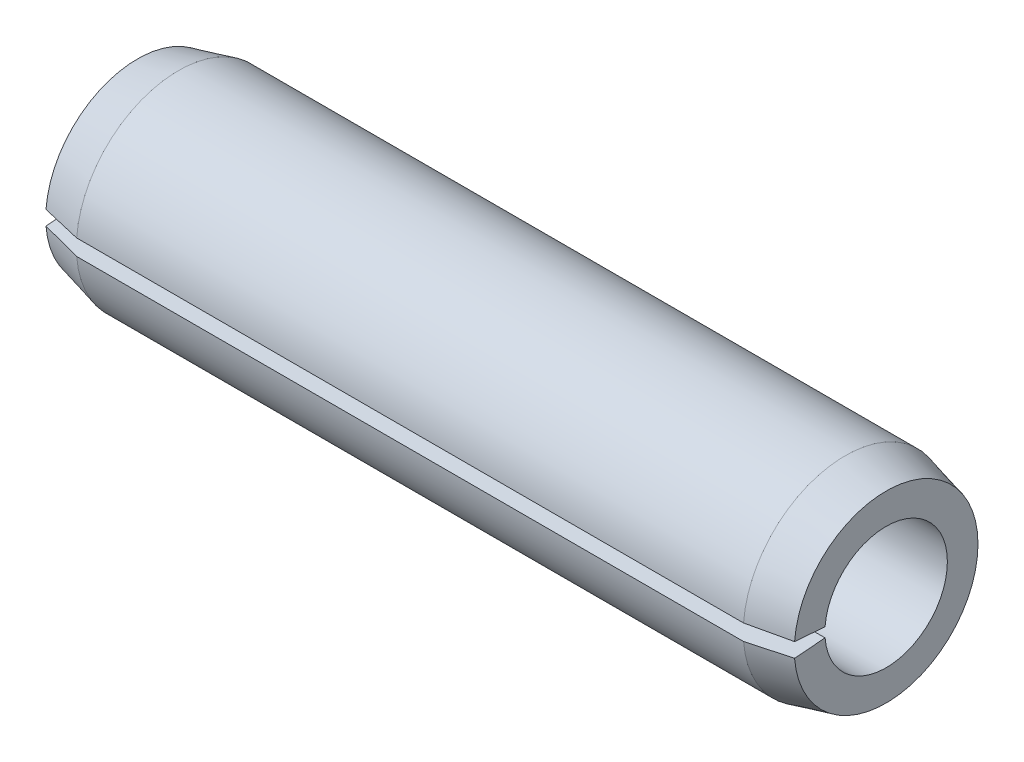
SolidWorks part; units mm, degrees
ref_plane "Plane1" through (0, 0, 0) normal (0, 0, 1) x (1, 0, 0)
ref_plane "Plane2" through (0, 0, 0) normal (0, 1, 0) x (1, 0, 0)
ref_plane "Plane3" through (0, 0, 0) normal (1, 0, 0) x (0, 0, -1)
other "Configuration Table"
sketch "Sketch1" plane through (0, 0, 0) normal (0, 0, 1) x (1, 0, 0)
  line L0 (-9.525, 0) -> (111.125, 0) construction
  line L1 (0, 1.8) -> (22, 1.8)
  line L2 (22, 1.8) -> (22, 2.7)
  line L3 (22, 2.7) -> (20.8, 3)
  line L4 (20.8, 3) -> (1.2, 3)
  line L5 (1.2, 3) -> (0, 2.7)
  line L7 (0, 2.7) -> (0, 1.8)
  dimension "Thickness" = 1.2
  dimension "Length" = 22
revolve "Base-Revolve" add sketch "Sketch1" angle 360 about L0
sketch "Sketch2" plane through (0, 0, 0) normal (-1, 0, 0) x (0, -1, 0)
  line L0 (0, 0) -> (0.2401, 3.0506)
  line L1 (0, -3.175) -> (0, 12.7) construction
  line L2 (0, 0) -> (-0.2401, 3.0506)
  arc A0 (0.2401, 3.0506) -> (-0.2401, 3.0506) centre (0, 0) ccw
  dimension "Gap_ang" = 9
extrude "Gap" cut sketch "Sketch2" against normal through all
equation "\"D1@Sketch2\" = \"Diameter@Sketch1\" * 0.51"
equation "\"D1@Sketch1\" = \"Diameter@Sketch1\" -  ( \"Thickness@Sketch1\" / 2 ) "
equation "\"D2@Sketch1\" = \"D1@Sketch1\""
equation "\"D3@Sketch1\" = \"Chamfer_len@Sketch1\""
